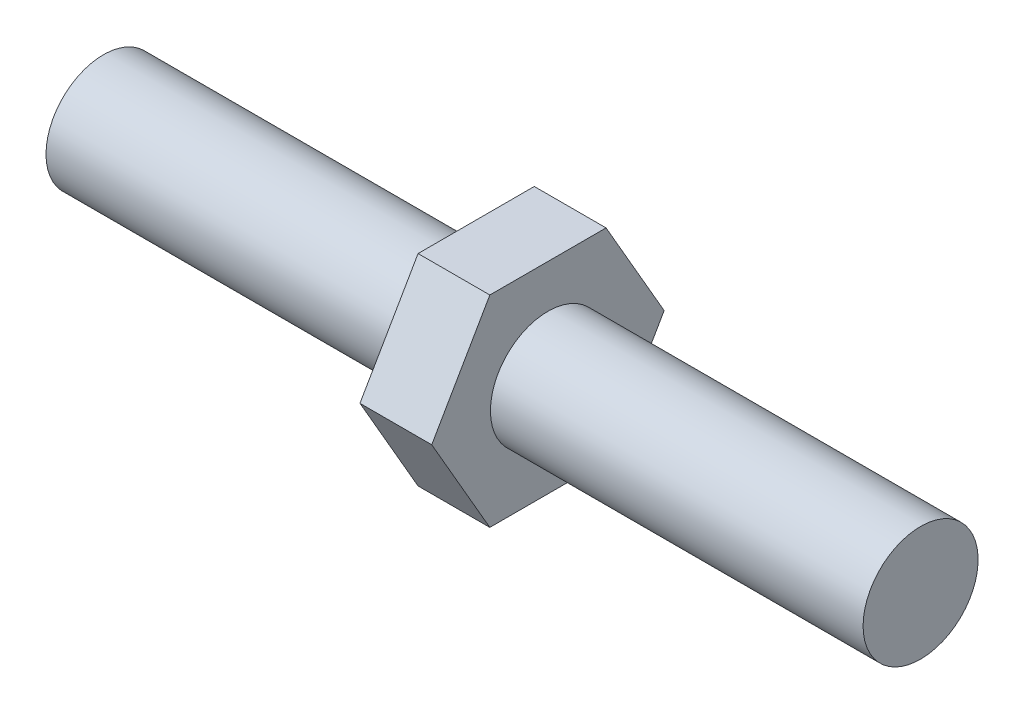
SolidWorks part; units mm, degrees
material "6061-T6 (SS)"
ref_plane "Front Plane" through (0, 0, 0) normal (0, 0, 1) x (1, 0, 0)
ref_plane "Top Plane" through (0, 0, 0) normal (0, 1, 0) x (1, 0, 0)
ref_plane "Right Plane" through (0, 0, 0) normal (1, 0, 0) x (0, 0, -1)
sketch "Sketch2" plane through (0, 0, 0) normal (0, 0, 1) x (1, 0, 0)
  line L0 (-22.5552, 0) -> (22.5552, 0) construction
  line L1 (-22.5552, 0) -> (-22.5552, 3.175)
  line L2 (-22.5552, 3.175) -> (-1.9812, 3.175)
  line L3 (-1.9812, 3.175) -> (-1.9812, 5.5562)
  line L4 (-1.9812, 5.5562) -> (1.9812, 5.5562)
  line L5 (1.9812, 5.5562) -> (1.9812, 3.175)
  line L6 (1.9812, 3.175) -> (22.5552, 3.175)
  line L7 (22.5552, 3.175) -> (22.5552, 0)
  line L8 (22.5552, 0) -> (-22.5552, 0)
  point P4 (0, 0)
  dimension "D1" = 3.9624
  dimension "D2" = 11.1125
  dimension "D3" = 45.1104
  dimension "D4" = 6.35
revolve "Revolve1" add sketch "Sketch2" angle 360 about L0
sketch "Sketch3" plane through (0, 0, 0) normal (1, 0, 0) x (0, 0, -1)
  line L1 (3.2079, -5.5563) -> (6.4158, 0)
  line L2 (6.4158, 0) -> (3.2079, 5.5563)
  line L3 (3.2079, 5.5563) -> (-3.2079, 5.5563)
  line L4 (-3.2079, 5.5563) -> (-6.4158, 0)
  line L5 (-6.4158, 0) -> (-3.2079, -5.5563)
  line L6 (-3.2079, -5.5563) -> (3.2079, -5.5563)
  circle A0 centre (0, 0) radius 5.5562 construction
  circle A1 centre (0, 0) radius 5.5562 construction
extrude "Boss-Extrude1" add sketch "Sketch3" along normal up to surface and the other way up to surface up to face at (1.9812, 0, 5.5562) other way up to face at (-1.9812, 0, 3.175)
ref_plane "Plane1" through (-9.8552, 0, 0) normal (-1, 0, 0) x (0, 0, 1)
ref_plane "Plane2" through (9.8552, 0, 0) normal (1, 0, 0) x (0, 0, -1)
